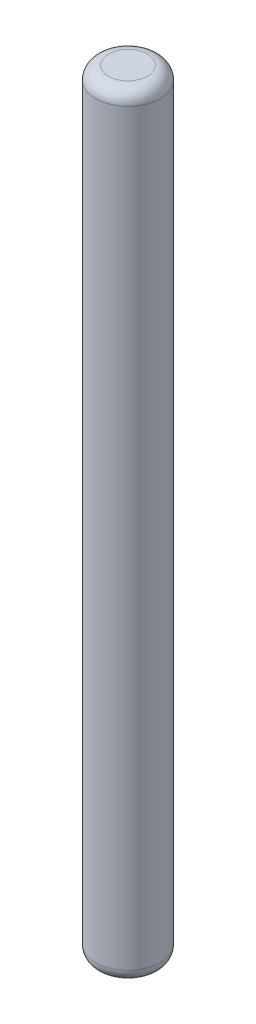
SolidWorks part; units mm, degrees
ref_plane "前视基准面" through (0, 0, 0) normal (0, 0, 1) x (1, 0, 0)
ref_plane "上视基准面" through (0, 0, 0) normal (0, 1, 0) x (1, 0, 0)
ref_plane "右视基准面" through (0, 0, 0) normal (1, 0, 0) x (0, 0, -1)
other "Configuration Table"
sketch "草图1" plane through (0, 0, 0) normal (0, 1, 0) x (1, 0, 0)
  circle A0 centre (0, 0) radius 2.5
  dimension "D1" = 5
extrude "凸台-拉伸1" add sketch "草图1" along normal blind 60
fillet "圆角1" radius 1 2 edges at (0, 0, 2.5) (0, 60, 2.5)
